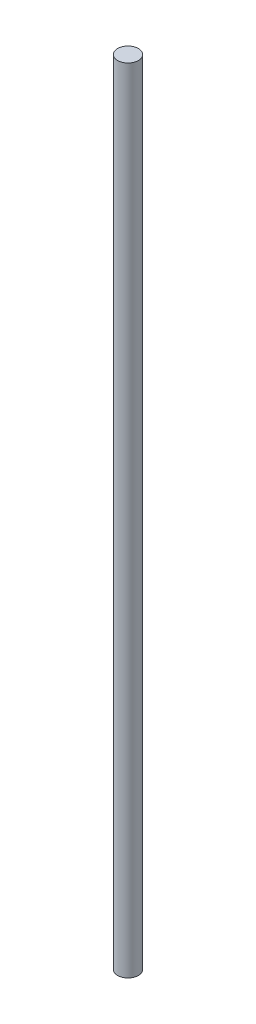
SolidWorks part; units mm, degrees
material "Chrome Stainless Steel"
ref_plane "Front Plane" through (0, 0, 0) normal (0, 0, 1) x (1, 0, 0)
ref_plane "Top Plane" through (0, 0, 0) normal (0, 1, 0) x (1, 0, 0)
ref_plane "Right Plane" through (0, 0, 0) normal (1, 0, 0) x (0, 0, -1)
sketch "Sketch1" plane through (0, 0, 0) normal (0, 1, 0) x (1, 0, 0)
  circle A0 centre (0, 0) radius 5
  dimension "D1" = 10
extrude "Boss-Extrude1" add sketch "Sketch1" along normal blind 380
